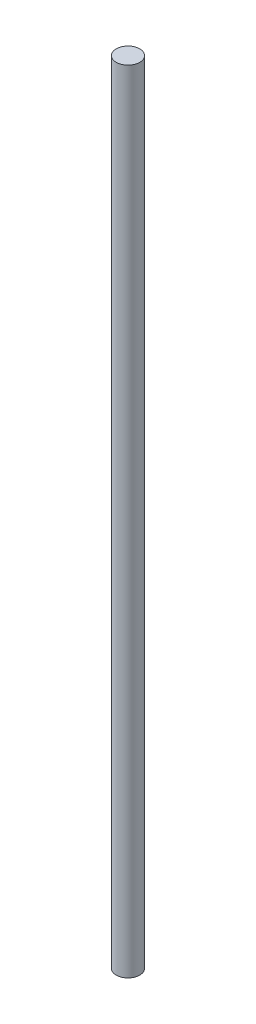
SolidWorks part; units mm, degrees
ref_plane "Ön Düzlem" through (0, 0, 0) normal (0, 0, 1) x (1, 0, 0)
ref_plane "Üst Düzlem" through (0, 0, 0) normal (0, 1, 0) x (1, 0, 0)
ref_plane "Sağ Düzlem" through (0, 0, 0) normal (1, 0, 0) x (0, 0, -1)
sketch "Çizim1" plane through (0, 0, 0) normal (0, 1, 0) x (1, 0, 0)
  circle A0 centre (0, 0) radius 2
  dimension "D1" = 4
extrude "Yükseklik-Ekstrüzyon1" add sketch "Çizim1" along normal blind 135
